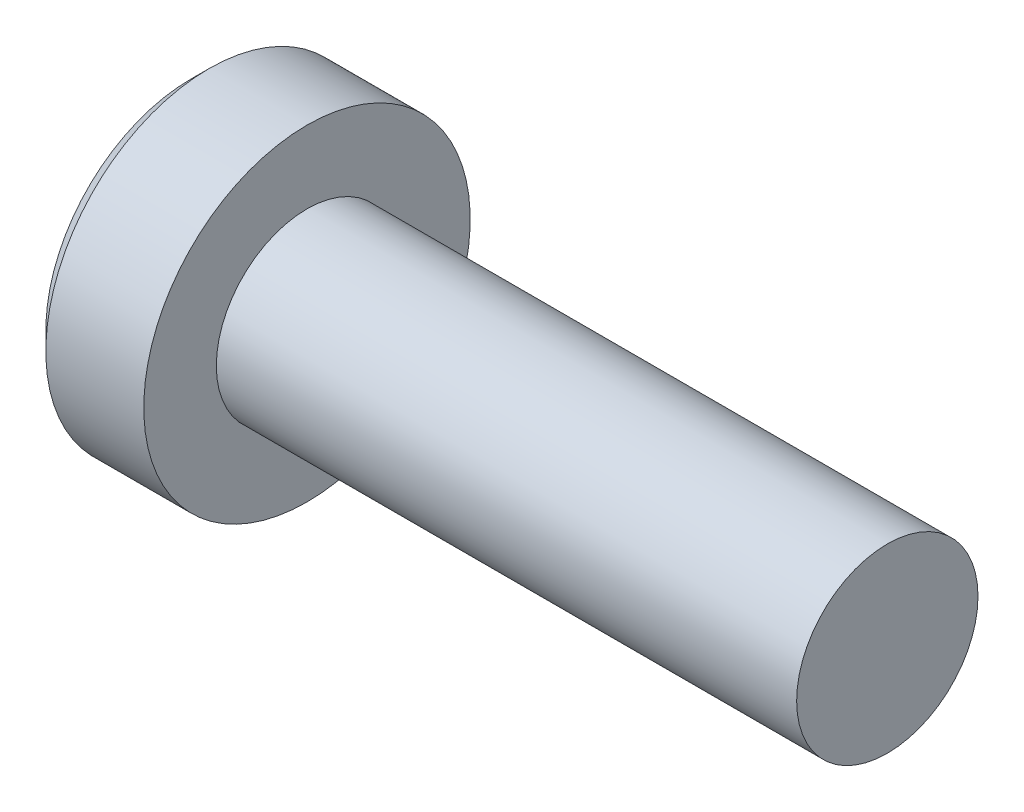
SolidWorks part; units mm, degrees
ref_plane "Front Plane" through (0, 0, 0) normal (0, 0, 1) x (1, 0, 0)
ref_plane "Top Plane" through (0, 0, 0) normal (0, 1, 0) x (1, 0, 0)
ref_plane "Right Plane" through (0, 0, 0) normal (1, 0, 0) x (0, 0, -1)
sketch "Sketch1" plane through (0, 0, 0) normal (0, 0, 1) x (1, 0, 0)
  line L0 (-1.6, 0) -> (8, 0) construction
  line L1 (8, 0) -> (8, 1.25)
  line L2 (8, 1.25) -> (0, 1.25)
  line L3 (0, 1.25) -> (0, 2.25)
  line L4 (0, 2.25) -> (-1.6, 2.25)
  line L5 (-1.6, 2.25) -> (-1.6, 0)
  line L6 (-1.6, 0) -> (8, 0)
  dimension "MSM_61" = 2.5
  dimension "MSM_62" = 4.5
  dimension "MSM_63" = 8
  dimension "MSM_64" = 1.6
revolve "Revolve1" add sketch "Sketch1" angle 360 about L0
cosmetic thread "Thread7" parameters "ATD"=2.013
sketch "Sketch2" plane through (-1.6, 0, 0) normal (-1, 0, 0) x (0, 0, 1)
  line L1 (0, 1.1547) -> (-1, 0.5774)
  line L2 (-1, 0.5774) -> (-1, -0.5774)
  line L3 (-1, -0.5774) -> (0, -1.1547)
  line L4 (0, -1.1547) -> (1, -0.5774)
  line L5 (1, -0.5774) -> (1, 0.5774)
  line L6 (1, 0.5774) -> (0, 1.1547)
  circle A0 centre (0, 0) radius 1 construction
  dimension "MSM_65" = 2
extrude "Cut-Extrude1" cut sketch "Sketch2" against normal blind 1.1
sketch "Sketch3" plane through (0, 0, 0) normal (0, 0, 1) x (1, 0, 0)
  line L0 (-0.5, 0) -> (0.0774, 0) construction
  line L1 (-0.5, -0.5774) -> (-0.5, 0.5774) construction
  line L2 (0.0774, 0) -> (-0.5, 1)
  line L3 (-0.5, 0.5774) -> (-0.5, 1.1547) construction
  line L4 (-0.5, 1) -> (-0.5, 0)
  line L5 (-0.5, 0) -> (0.0774, 0)
  dimension "FIX_2" = 30
  dimension "FIX_3" = 2
revolve "Cut-Revolve1" cut sketch "Sketch3" angle 360 about L0
chamfer "Chamfer1" distance 0.25 1 edges at (-1.6, -2.25, 0)
equation "\"FIX_5@Chamfer1\" = \"MSM_61@Sketch1\" / 10"
equation "\"FIX_3@Sketch3\" = \"MSM_65@Sketch2\""
